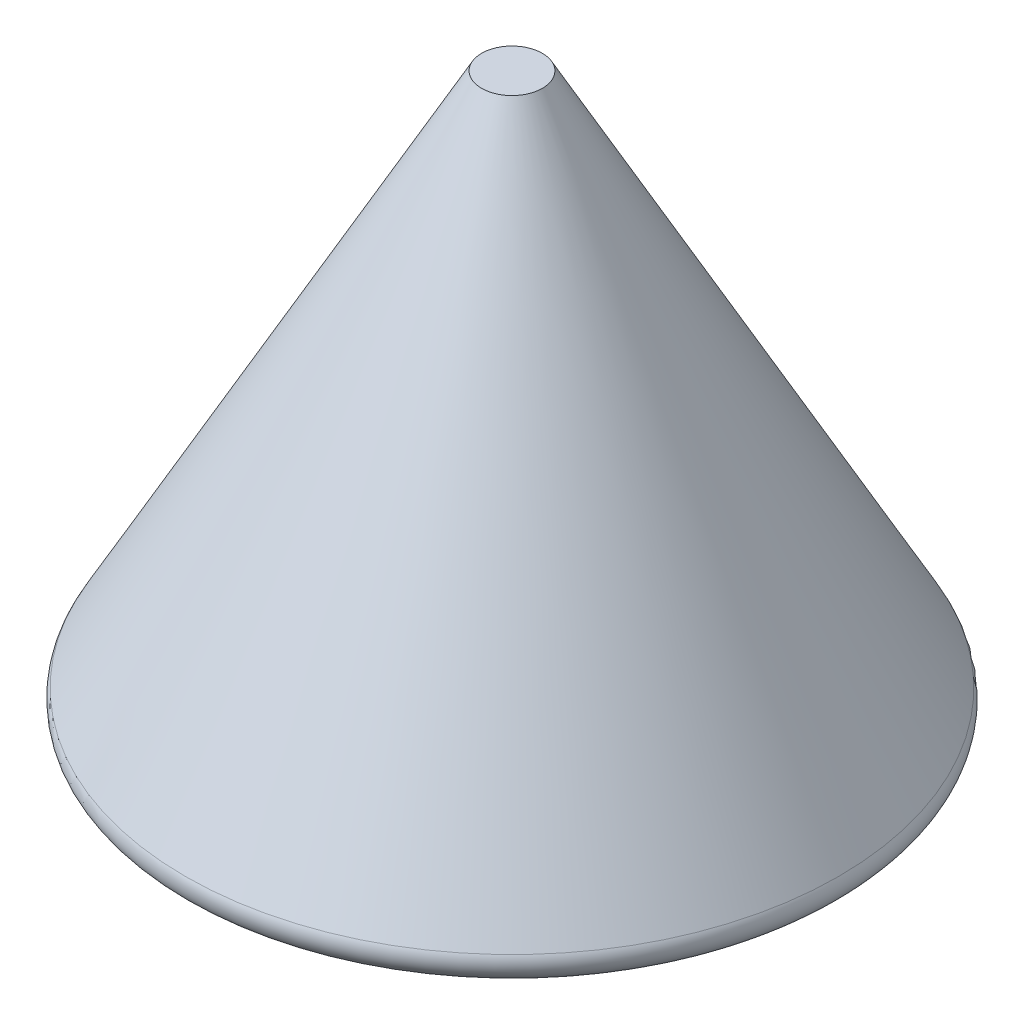
SolidWorks part; units mm, degrees
ref_plane "Front Plane" through (0, 0, 0) normal (0, 0, 1) x (1, 0, 0)
ref_plane "Top Plane" through (0, 0, 0) normal (0, 1, 0) x (1, 0, 0)
ref_plane "Right Plane" through (0, 0, 0) normal (1, 0, 0) x (0, 0, -1)
sketch "Sketch1" plane through (0, 0, 0) normal (0, 1, 0) x (1, 0, 0)
  circle A0 centre (0, 0) radius 36.5
  dimension "D1" = 73
extrude "Boss-Extrude1" add sketch "Sketch1" along normal blind 60 draft 29
fillet "Fillet1" radius 2 1 edges at (0, 0, 36.5)
